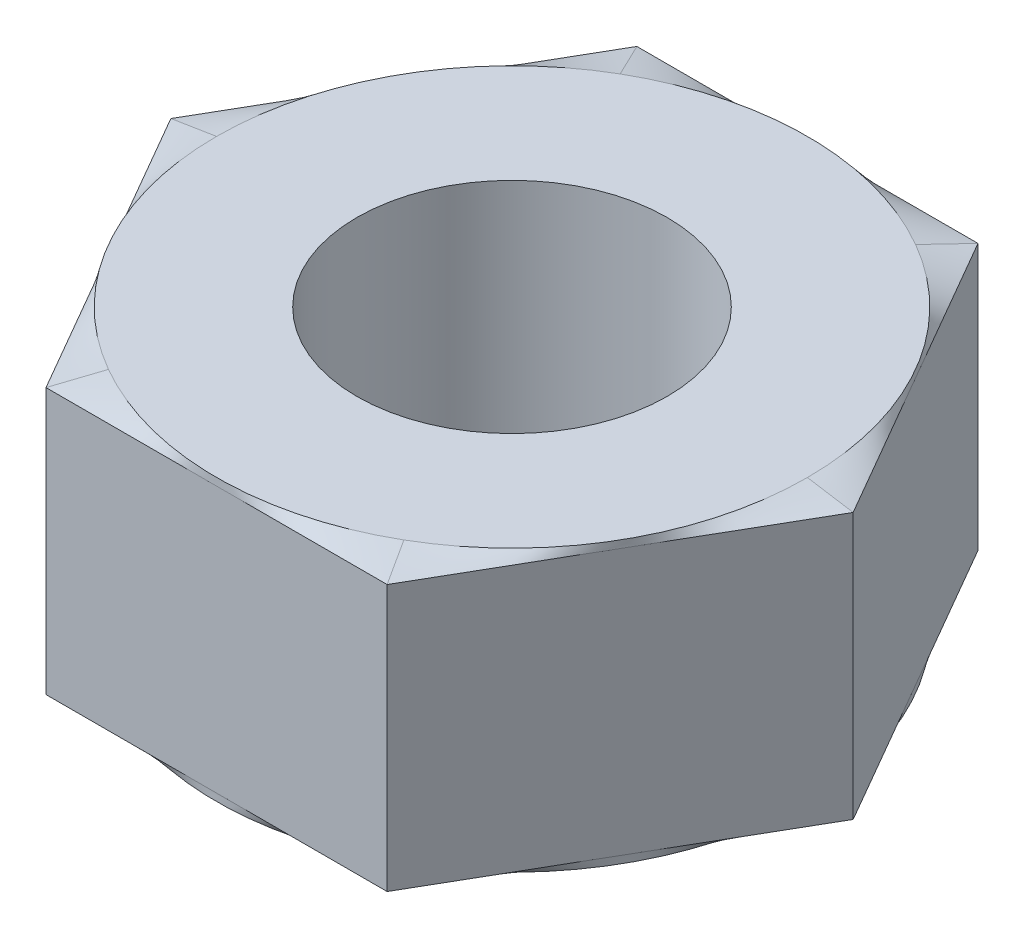
SolidWorks part; units mm, degrees
ref_plane "前视" through (0, 0, 0) normal (0, 0, 1) x (1, 0, 0)
ref_plane "上视" through (0, 0, 0) normal (0, 1, 0) x (1, 0, 0)
ref_plane "右视" through (0, 0, 0) normal (1, 0, 0) x (0, 0, -1)
sketch "草图1" plane through (0, 0, 0) normal (0, 1, 0) x (1, 0, 0)
  line L0 (-4.0854, 0) -> (3.3721, 0) construction
  line L1 (4.6188, 0) -> (2.3094, 4)
  line L2 (2.3094, 4) -> (-2.3094, 4)
  line L3 (-2.3094, 4) -> (-4.6188, 0)
  line L4 (-4.6188, 0) -> (-2.3094, -4)
  line L5 (-2.3094, -4) -> (2.3094, -4)
  line L6 (2.3094, -4) -> (4.6188, 0)
  circle A0 centre (0, 0) radius 4 construction
  dimension "D1" = 8
extrude "凸台-拉伸1" add sketch "草图1" along normal blind 1.8
ref_plane "基准面1" through (0, -0.1, 0) normal (0, -1, 0) x (-1, 0, 0)
sketch "草图3" plane through (0, 0, 0) normal (0, -1, 0) x (1, 0, 0)
  line L6 (4.6188, 0) -> (2.3094, 4)
  line L7 (2.3094, 4) -> (-2.3094, 4)
  line L8 (-2.3094, 4) -> (-4.6188, 0)
  line L9 (-4.6188, 0) -> (-2.3094, -4)
  line L10 (-2.3094, -4) -> (2.3094, -4)
  line L11 (2.3094, -4) -> (4.6188, 0)
  line L12 (4.6188, 0) -> (2.3094, 4)
  line L13 (2.3094, 4) -> (-2.3094, 4)
  line L14 (-2.3094, 4) -> (-4.6188, 0)
  line L15 (-4.6188, 0) -> (-2.3094, -4)
  line L16 (-2.3094, -4) -> (2.3094, -4)
  line L17 (2.3094, -4) -> (4.6188, 0)
  dimension "D1" = 0
sketch "草图4" plane through (0, -0.1, 0) normal (0, -1, 0) x (-1, 0, 0)
  line L0 (4.6188, 0) -> (2.3094, 4) construction
  line L1 (4.6188, 0) -> (2.3094, 4) construction
  circle A0 centre (0, 0) radius 4
loft "放样1" add profiles "草图4", "草图3"
ref_plane "基准面2" through (0, 1.8, 0) normal (0, 1, 0) x (1, 0, 0)
mirror "镜向1" about plane through (0, 1.8, 0) normal (0, 1, 0) of "凸台-拉伸1", "放样1"
sketch "草图5" plane through (0, -0.1, 0) normal (0, 1, 0) x (1, 0, 0)
  circle A0 centre (0, 0) radius 2.1
  dimension "D1" = 4.2
extrude "切除-拉伸1" cut sketch "草图5" along normal through all
cosmetic thread "孔螺蚊线2" parameters "D2"=5
hole_wizard "M5 螺纹孔1" positions "3D草图1" profile "草图6" tap size "M5" standard "ISO" end condition through all
sketch3d "3D草图1"
  line L0 (0, 3.7, 0) -> (0, -0.1, 0) construction
  line L1 (0, 3.7, 0) -> (0, -0.1, 0) construction
  line L2 (0, 3.7, 0) -> (0, -0.1, 0) construction
  point P0 (0, 3.7, 0)
sketch "草图6" plane through (0, 3.7, 0) normal (1, 0, 0) x (0, 0, 1)
  line L0 (0, 0) -> (0, 3.8019)
  line L1 (0, 3.8019) -> (2.1, 3.8019)
  line L2 (2.1, 3.8019) -> (2.1, 0)
  line L5 (2.1, 0) -> (0, 0)
  line L11 (0, -6.35) -> (0, 107.95) construction
  dimension "通孔螺纹孔钻头直径" = 4.2
  dimension "通孔螺纹孔钻头深度" = 3.8019
move or copy body "实体-移动/复制1" bodies to move or copy 106
